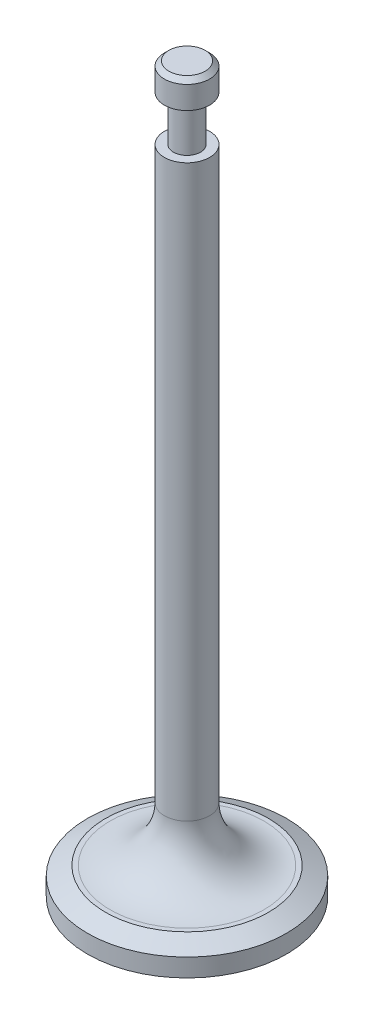
SolidWorks part; units mm, degrees
ref_plane "Front Plane" through (0, 0, 0) normal (0, 0, 1) x (1, 0, 0)
ref_plane "Top Plane" through (0, 0, 0) normal (0, 1, 0) x (1, 0, 0)
ref_plane "Right Plane" through (0, 0, 0) normal (1, 0, 0) x (0, 0, -1)
sketch "Sketch1" plane through (0, 0, 0) normal (1, 0, 0) x (0, 0, -1)
  line L0 (0, 0) -> (0, -80)
  line L1 (0, -80) -> (11, -80)
  line L2 (11, -80) -> (11, -77)
  line L3 (11, -77) -> (2.5, -77)
  line L4 (2.5, -77) -> (2.5, -8)
  line L5 (2.5, -8) -> (1.5, -8)
  line L6 (1.5, -8) -> (1.5, -3)
  line L7 (1.5, -3) -> (2.5, -3)
  line L8 (2.5, -3) -> (2.5, 0)
  line L9 (2.5, 0) -> (0, 0)
  dimension "D1" = 80
  dimension "D2" = 11
  dimension "D3" = 3
  dimension "D4" = 2.5
  dimension "D5" = 3
  dimension "D6" = 5
  dimension "D7" = 1
  dimension "D8" = 2.5
revolve "Revolve1" add sketch "Sketch1" angle 360 about L0
fillet "Fillet1" radius 6 1 edges at (0, -77, 2.5)
chamfer "Chamfer1" distance 1 distance2 2 1 edges at (0, -77, 11)
chamfer "Chamfer2" distance 0.5 angle 45 1 edges at (0, 0, 2.5)
